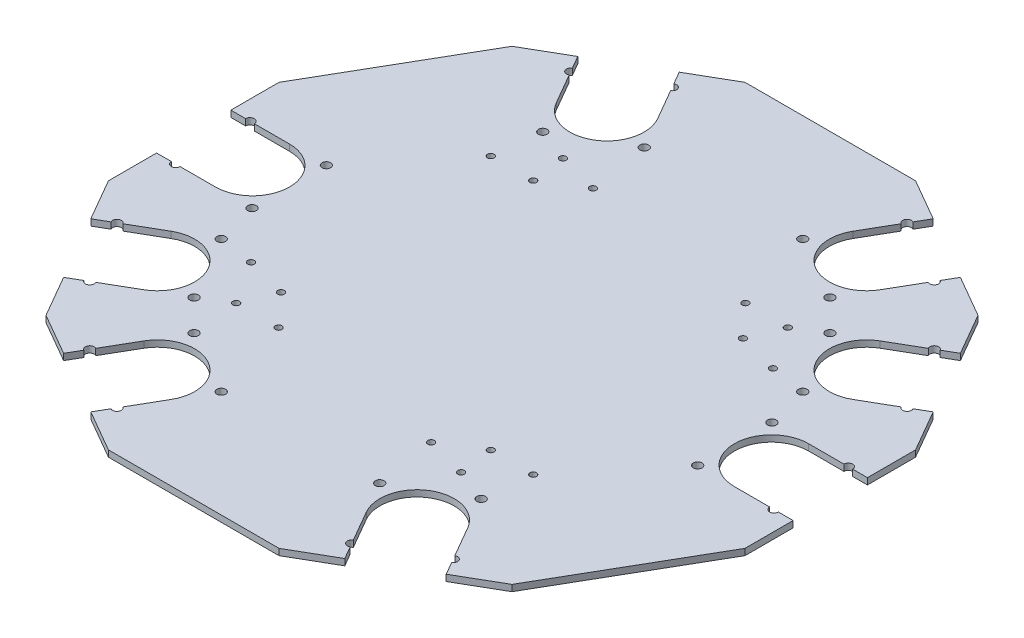
SolidWorks part; units mm, degrees
material "CF-ntbk"
ref_plane "Front Plane" through (0, 0, 0) normal (0, 0, 1) x (1, 0, 0)
ref_plane "Top Plane" through (0, 0, 0) normal (0, 1, 0) x (1, 0, 0)
ref_plane "Right Plane" through (0, 0, 0) normal (1, 0, 0) x (0, 0, -1)
sketch "Sketch1" plane through (0, 0, 0) normal (0, 1, 0) x (1, 0, 0)
  line L19 (150, -40.1924) -> (150, 40.1924)
  line L20 (150, 40.1924) -> (109.8076, 109.8076)
  line L21 (109.8076, 109.8076) -> (40.1924, 150)
  line L22 (40.1924, 150) -> (-40.1924, 150)
  line L23 (-40.1924, 150) -> (-109.8076, 109.8076)
  line L24 (-109.8076, 109.8076) -> (-150, 40.1924)
  line L25 (-150, 40.1924) -> (-150, -40.1924)
  line L26 (-150, -40.1924) -> (-109.8076, -109.8076)
  line L27 (-109.8076, -109.8076) -> (-40.1924, -150)
  line L28 (-40.1924, -150) -> (40.1924, -150)
  line L29 (40.1924, -150) -> (109.8076, -109.8076)
  line L30 (109.8076, -109.8076) -> (150, -40.1924)
  line L33 (-44.2539, 0) -> (44.2539, 0) construction
  circle A0 centre (0, 0) radius 150 construction
  dimension "D1" = 300
  dimension "D2" = 90
extrude "Boss-Extrude1" add sketch "Sketch1" along normal blind 3
sketch "Sketch2" plane through (0, 3, 0) normal (0, 1, 0) x (1, 0, 0)
  line L0 (-79.7985, -138.215) -> (79.7985, 138.215) construction
  line L1 (46.2229, 94.5567) -> (65.2799, 83.5542) construction
  line L2 (-69.8318, 120.9522) -> (69.8318, -120.9522) construction
  line L3 (0, -44.7868) -> (0, 44.7868) construction
  line L5 (-44.2539, 0) -> (44.2539, 0) construction
  line L6 (-150.8166, 0) -> (150.8166, 0) construction
  line L7 (-118.217, -118.217) -> (118.217, 118.217) construction
  line L8 (-102.6144, 102.6144) -> (102.6144, -102.6144) construction
  line L9 (105, 17.5) -> (105, -8.6918) construction
  line L11 (48.1946, -93.4184) -> (56.6973, -88.5094) construction
  circle A0 centre (55.3446, 130.8596) radius 2.05
  circle A1 centre (37.3446, 99.6827) radius 2.05
  circle A2 centre (37.3446, -99.6827) radius 2.05
  circle A3 centre (55.3446, -130.8596) radius 2.05
  circle A4 centre (105, 17.5) radius 2.05
  circle A5 centre (141, 17.5) radius 2.05
  circle A12 centre (105, -17.5) radius 2.05
  circle A13 centre (141, -17.5) radius 2.05
  circle A16 centre (85.6554, -113.3596) radius 2.05
  circle A17 centre (67.6554, -82.1827) radius 2.05
  circle A18 centre (85.6554, 113.3596) radius 2.05
  circle A19 centre (67.6554, 82.1827) radius 2.05
  dimension "D1" = 4.1
  dimension "D2" = 36
  dimension "D3" = 30
  dimension "D5" = 30
  dimension "D6" = 36
  dimension "D8" = 36
  dimension "D10" = 45
  dimension "D11" = 45
  dimension "D4" = 17.5
  dimension "D7" = 105
  dimension "D9" = 17.5
  dimension "D15" = 105
  dimension "D17" = 105
  dimension "D20" = 17.5
  dimension "D21" = 17.5
  dimension "D24" = 17.5
  dimension "D25" = 17.5
  dimension "D29" = 17.5
  dimension "D30" = 17.5
  dimension "D31" = 36
  dimension "D12" = 17.5
  dimension "D13" = 17.5
  dimension "D14" = 36
  dimension "D16" = 17.5
  dimension "D18" = 17.5
  dimension "D19" = 36
extrude "HexCut1" cut sketch "Sketch2" against normal up to surface (3 mm away) up to face at (0, 0, 0)
mirror "HexCut2" about plane through (0, 0, 0) normal (1, 0, 0) of "HexCut1"
sketch "ConstructLines" plane through (0, 3, 0) normal (0, 1, 0) x (1, 0, 0)
  line L0 (0, 121.6855) -> (0, -121.6855) construction
  line L1 (-91.1915, 0) -> (91.1915, 0) construction
  line L2 (-44.2539, 0) -> (44.2539, 0) construction
  line L3 (-70.8661, 122.7437) -> (70.8661, -122.7437) construction
  line L4 (-122.7437, -70.8661) -> (122.7437, 70.8661) construction
  line L5 (-33.6706, -125.6604) -> (33.6706, 125.6604) construction
  line L6 (-132.6309, 35.5383) -> (132.6309, -35.5383) construction
  dimension "D1" = 30
  dimension "D2" = 45
  dimension "D3" = 90
ref_point "Point1"
sketch "Sketch5" plane through (0, 3, 0) normal (0, 1, 0) x (1, 0, 0)
  line L0 (0, 121.6855) -> (0, -121.6855) construction
  line L1 (-91.1915, 0) -> (91.1915, 0) construction
  circle A0 centre (50, 60) radius 1.55
  circle A1 centre (70, 60) radius 1.55
  dimension "D1" = 3.1
  dimension "D2" = 20
  dimension "D3" = 50
  dimension "D4" = 60
  dimension "D5" = 60
extrude "RailMountHoles" cut sketch "Sketch5" against normal up to surface (3 mm away) up to face at (-55.3446, 0, -128.8096)
pattern_linear "LPattern1" count 2 spacing 120 along (0, 0, 1) count 2 spacing 120 along (-1, 0, 0) of "RailMountHoles"
sketch "Sketch6" plane through (0, 3, 0) normal (0, 1, 0) x (1, 0, 0)
  line L0 (-126.2708, -72.9025) -> (126.2708, 72.9025) construction
  line L1 (0, 121.6855) -> (0, -121.6855) construction
  line L2 (87.7927, 57.9385) -> (95.9037, 43.89) construction
  line L3 (-69.5169, 120.4068) -> (69.5169, -120.4068) construction
  circle A0 centre (99.6827, 37.3446) radius 2.05
  circle A1 centre (130.8596, 55.3446) radius 2.05
  circle A2 centre (113.3596, 85.6554) radius 2.05
  circle A3 centre (82.1827, 67.6554) radius 2.05
  dimension "D4" = 4.1
  dimension "D1" = 60
  dimension "D2" = 105
  dimension "D3" = 36
  dimension "D5" = 17.5
  dimension "D6" = 17.5
  dimension "D7" = 17.5
  dimension "D8" = 17.5
  dimension "D9" = 36
  dimension "D17" = 30
extrude "QuadCut1" cut sketch "Sketch6" against normal up to surface (3 mm away) up to face at (70, 0, 61.55)
ref_plane "MirrorPlaneQuad" through (0, 0, 0) normal (0.866, 0, -0.5) x (-0.5, 0, -0.866)
mirror "Mirror1" about plane through (0, 0, 0) normal (0.866, 0, -0.5) of "QuadCut1"
sketch "Sketch7" plane through (0, 3, 0) normal (0, 1, 0) x (1, 0, 0)
  line L0 (45.9946, 114.6649) -> (83.4946, 179.6168)
  line L1 (83.4946, 179.6168) -> (113.8054, 162.1168)
  line L2 (113.8054, 162.1168) -> (76.3054, 97.1649)
  line L3 (37.3446, 99.6827) -> (67.6554, 82.1827) construction
  line L4 (105, 17.5) -> (105, -17.5) construction
  line L5 (37.3446, -99.6827) -> (67.6554, -82.1827) construction
  line L6 (45.9946, -114.6649) -> (83.4946, -179.6168)
  line L7 (76.3054, -97.1649) -> (113.8054, -162.1168)
  line L8 (83.4946, -179.6168) -> (113.8054, -162.1168)
  line L9 (122.3, 17.5) -> (162.3, 17.5)
  line L10 (162.3, 17.5) -> (162.3, -17.5)
  line L11 (162.3, -17.5) -> (122.3, -17.5)
  arc A0 (45.9946, 114.6649) -> (76.3054, 97.1649) centre (61.15, 105.9149) ccw
  circle A1 centre (85.6554, -113.3596) radius 2.05 construction
  arc A2 (122.3, 17.5) -> (122.3, -17.5) centre (122.3, 0) ccw
  circle A3 centre (55.3446, 130.8596) radius 2.05 construction
  circle A4 centre (85.6554, 113.3596) radius 2.05 construction
  arc A6 (76.3054, -97.1649) -> (45.9946, -114.6649) centre (61.15, -105.9149) ccw
  circle A7 centre (55.3446, -130.8596) radius 2.05 construction
  dimension "D1" = 0
  dimension "D3" = 0
  dimension "D4" = 35
  dimension "D6" = 35
  dimension "D7" = 0
  dimension "D12" = 0
  dimension "D2" = 75
  dimension "D5" = 17.3
  dimension "D8" = 75
  dimension "D9" = 17.3
  dimension "D10" = 17.3
  dimension "D11" = 40
extrude "Cut-Extrude3" cut sketch "Sketch7" against normal up to surface (3 mm away) up to face at (-82.1827, 0, 69.7054)
mirror "Mirror2" about plane through (0, 0, 0) normal (1, 0, 0) of "Cut-Extrude3"
sketch "Sketch8" plane through (0, 3, 0) normal (0, 1, 0) x (1, 0, 0)
  line L0 (82.1827, 67.6554) -> (99.6827, 37.3446) construction
  line L1 (97.1649, 76.3054) -> (131.8059, 96.3054)
  line L2 (131.8059, 96.3054) -> (149.3059, 65.9946)
  line L3 (149.3059, 65.9946) -> (114.6649, 45.9946)
  arc A0 (97.1649, 76.3054) -> (114.6649, 45.9946) centre (105.9149, 61.15) ccw
  circle A1 centre (130.8596, 55.3446) radius 2.05 construction
  circle A2 centre (113.3596, 85.6554) radius 2.05 construction
  dimension "D1" = 35
  dimension "D2" = 17.3
  dimension "D3" = 40
  dimension "D4" = 0
  dimension "D5" = 0
extrude "Cut-Extrude4" cut sketch "Sketch8" against normal up to surface (3 mm away) up to face at (0, 0, 0)
mirror "Mirror3" about plane through (0, 0, 0) normal (0.866, 0, -0.5) of "Cut-Extrude4"
sketch "Sketch9" plane through (0, 3, 0) normal (0, 1, 0) x (1, 0, 0)
  line L0 (-132.6309, 35.5383) -> (132.6309, -35.5383) construction
  line L1 (-33.6706, -125.6604) -> (33.6706, 125.6604) construction
  circle A0 centre (63.8254, 45.0146) radius 1.55
  circle A1 centre (83.144, 39.8382) radius 1.55
  dimension "D5" = 60
  dimension "D2" = 3.1
  dimension "D1" = 20
  dimension "D3" = 60
  dimension "D4" = 50
extrude "Cut-Extrude5" cut sketch "Sketch9" against normal up to surface (3 mm away) up to face at (0, 0, 0)
ref_plane "RailQuadXPlane" through (0, 0, 0) normal (0.2588, 0, -0.9659) x (-0.9659, 0, -0.2588)
ref_plane "RailQuadZPlane" through (0, 0, 0) normal (0.9659, 0, 0.2588) x (0.2588, 0, -0.9659)
mirror "Mirror4" about plane through (0, 0, 0) normal (0.2588, 0, -0.9659) of "Cut-Extrude5"
mirror "Mirror5" about plane through (0, 0, 0) normal (0.9659, 0, 0.2588) of "Cut-Extrude5"
mirror "Mirror6" about plane through (0, 0, 0) normal (0.9659, 0, 0.2588) of "Mirror4"
equation "\"ClampHoleDist\"= 36"
equation "\"D2@Sketch2\"=\"ClampHoleDist\""
equation "\"ClampDistMid\"=105"
equation "\"Length\"= 300"
equation "\"Width\"= 200"
equation "\"D8@Sketch2\"=\"ClampHoleDist\""
equation "\"D6@Sketch2\"=\"ClampHoleDist\""
equation "\"RailHoleZDist\"= 60.000000"
equation "\"D5@Sketch5\"=\"RailHoleZDist\""
equation "\"D4@Sketch5\"=\"RailHoleZDist\""
equation "\"RailHoleXDist\"= 50.000000"
equation "\"D3@Sketch5\"=\"RailHoleXDist\""
equation "\"RailHoleSpacing\"= 20"
equation "\"D2@Sketch5\"=\"RailHoleSpacing\""
equation "\"D3@LPattern1\"=\"RailHoleZDist\"*2"
equation "\"D4@LPattern1\"=\"RailHoleXDist\"*2+(\"RailHoleSpacing\")"
equation "\"ClampHoriDist\"=17.5"
equation "\"D4@Sketch2\"=\"ClampHoriDist\""
equation "\"D9@Sketch2\"=\"ClampHoriDist\""
equation "\"D7@Sketch2\"=\"ClampDistMid\""
equation "\"D15@Sketch2\"=\"ClampDistMid\""
equation "\"D17@Sketch2\"=\"ClampDistMid\""
equation "\"D20@Sketch2\"=\"ClampHoriDist\""
equation "\"D21@Sketch2\"=\"ClampHoriDist\""
equation "\"D24@Sketch2\"=\"ClampHoriDist\""
equation "\"D25@Sketch2\"=\"ClampHoriDist\""
equation "\"D29@Sketch2\"=\"ClampHoriDist\""
equation "\"D30@Sketch2\"=\"ClampHoriDist\""
equation "\"D31@Sketch2\"=\"ClampHoleDist\""
equation "\"D12@Sketch2\"=\"ClampHoriDist\""
equation "\"D13@Sketch2\"=\"ClampHoriDist\""
equation "\"D14@Sketch2\"=\"ClampHoleDist\""
equation "\"ClampHoleSize\"=4.1"
equation "\"D1@Sketch2\"=\"ClampHoleSize\""
equation "\"D16@Sketch2\"=\"ClampHoriDist\""
equation "\"D19@Sketch2\"=\"ClampHoleDist\""
equation "\"D18@Sketch2\"=\"ClampHoriDist\""
equation "\"D2@Sketch6\"=\"ClampDistMid\""
equation "\"D3@Sketch6\"=\"ClampHoleDist\""
equation "\"D4@Sketch6\"=\"ClampHoleSize\""
equation "\"D5@Sketch6\"=\"ClampHoriDist\""
equation "\"D6@Sketch6\"=\"ClampHoriDist\""
equation "\"D7@Sketch6\"=\"ClampHoriDist\""
equation "\"D8@Sketch6\"=\"ClampHoriDist\""
equation "\"D9@Sketch6\"=\"ClampHoleDist\""
equation "\"TubeOutDiam\"= 25.1"
equation "\"D1@Sketch8\"=\"TubeOutDiam\"+ 9.9"
equation "\"D1@Sketch1\"=\"Length\""
equation "\"RailHoleDiam\"=3.1"
equation "\"D1@Sketch5\"=\"RailHoleDiam\""
equation "\"D1@Sketch9\"=\"RailHoleSpacing\""
equation "\"D2@Sketch9\"=\"RailHoleDiam\""
equation "\"D3@Sketch9\"=\"RailHoleZDist\""
equation "\"D4@Sketch9\"=\"RailHoleXDist\""
equation "\"D5@Sketch9\"=\"RailHoleZDist\""
